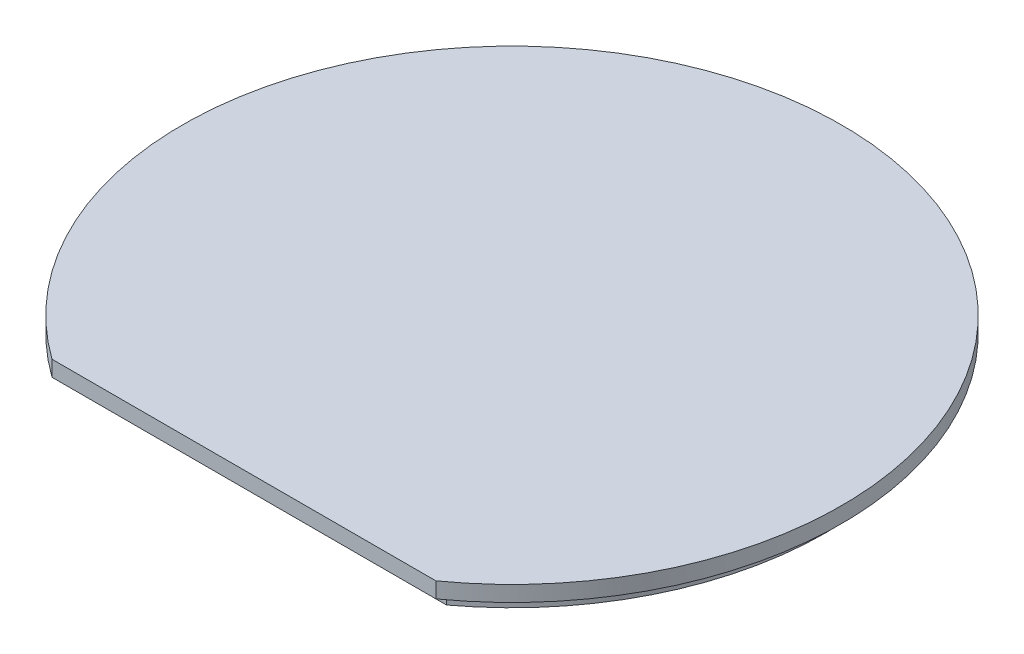
SolidWorks part; units mm, degrees
ref_plane "Front Plane" through (0, 0, 0) normal (0, 0, 1) x (1, 0, 0)
ref_plane "Top Plane" through (0, 0, 0) normal (0, 1, 0) x (1, 0, 0)
ref_plane "Right Plane" through (0, 0, 0) normal (1, 0, 0) x (0, 0, -1)
sketch "Sketch2" plane through (0, 0, 0) normal (0, 1, 0) x (1, 0, 0)
  line L0 (-29.2031, -40.7886) -> (29.2031, -40.7886)
  arc A0 (29.2031, -40.7886) -> (-29.2031, -40.7886) centre (0, 0) ccw
  dimension "D1" = 100.33
  dimension "D2" = 58.4062
extrude "Boss-Extrude1" add sketch "Sketch2" along normal mid plane 4.7625
sketch "Sketch3" plane through (0, -2.3813, 0) normal (0, -1, 0) x (1, 0, 0)
  line L0 (-28.4282, 38.4073) -> (28.4282, 38.4073)
  line L1 (-29.2031, 40.7886) -> (29.2031, 40.7886) construction
  arc A0 (-28.4282, 38.4073) -> (28.4282, 38.4073) centre (0, 0) ccw
  arc A1 (-29.2031, 40.7886) -> (29.2031, 40.7886) centre (0, 0) ccw construction
  dimension "D1" = 2.3813
  dimension "D2" = 2.3813
extrude "Cut-Extrude1" cut sketch "Sketch3" against normal blind 2.3813 flip side to cut
